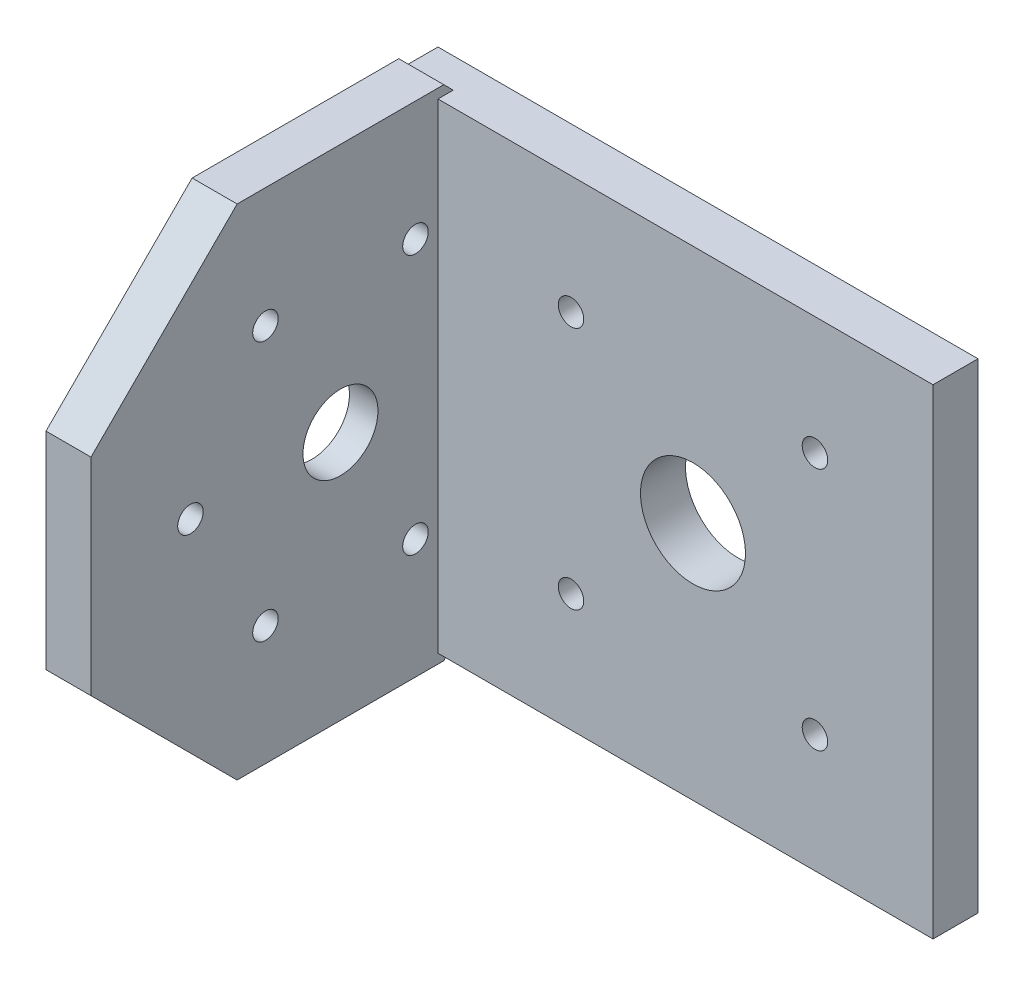
SolidWorks part; units mm, degrees
ref_plane "Front Plane" through (0, 0, 0) normal (0, 0, 1) x (1, 0, 0)
ref_plane "Top Plane" through (0, 0, 0) normal (0, 1, 0) x (1, 0, 0)
ref_plane "Right Plane" through (0, 0, 0) normal (1, 0, 0) x (0, 0, -1)
ref_plane "PL_Roll_Plate_base" through (-40, 0, 0) normal (1, 0, 0) x (0, 0, -1)
sketch "SK_Roll_Plate" plane through (-40, 0, 0) normal (1, 0, 0) x (0, 0, -1)
  line L0 (-13.7766, 33.2597) -> (-33.2597, 13.7766)
  line L1 (-33.2597, 13.7766) -> (-33.2597, -13.7766)
  line L2 (-33.2597, -13.7766) -> (-13.7766, -33.2597)
  line L3 (-13.7766, -33.2597) -> (13.7766, -33.2597)
  line L4 (13.7766, -33.2597) -> (33.2597, -13.7766)
  line L5 (33.2597, -13.7766) -> (33.2597, 13.7766)
  line L6 (33.2597, 13.7766) -> (13.7766, 33.2597)
  line L7 (13.7766, 33.2597) -> (-13.7766, 33.2597)
  circle A0 centre (20, 0) radius 1.7
  circle A1 centre (10, 17.3205) radius 1.7
  circle A2 centre (-10, 17.3205) radius 1.7
  circle A3 centre (-20, 0) radius 1.7
  circle A4 centre (-10, -17.3205) radius 1.7
  circle A5 centre (10, -17.3205) radius 1.7
  circle A6 centre (0, 0) radius 5
  dimension "D17_SK_Roll_Plate" = 3.4
  dimension "D19_SK_Roll_Plate" = 3.4
  dimension "D22_SK_Roll_Plate" = 3.4
  dimension "D25_SK_Roll_Plate" = 3.4
  dimension "D27_SK_Roll_Plate" = 3.4
  dimension "D30_SK_Roll_Plate" = 3.4
  dimension "D33_SK_Roll_Plate" = 10
  dimension "P1" = 13.7766
  dimension "P2" = 33.2597
  dimension "P3" = 33.2597
  dimension "P4" = 13.7766
  dimension "P5" = 33.2597
  dimension "P6" = 13.7766
  dimension "P7" = 13.7766
  dimension "P8" = 33.2597
  dimension "P9" = 13.7766
  dimension "P10" = 33.2597
  dimension "P11" = 33.2597
  dimension "P12" = 13.7766
  dimension "P13" = 33.2597
  dimension "P14" = 13.7766
  dimension "P15" = 13.7766
  dimension "P16" = 33.2597
  dimension "P18" = 20
  dimension "P20" = 10
  dimension "P21" = 17.3205
  dimension "P23" = 10
  dimension "P24" = 17.3205
  dimension "P26" = 20
  dimension "P28" = 10
  dimension "P29" = 17.3205
  dimension "P31" = 10
  dimension "P32" = 17.3205
extrude "Roll_Plate" add sketch "SK_Roll_Plate" along normal blind 6
ref_plane "PL_Yaw_Plate_base" through (0, 0, -19) normal (0, 0, 1) x (1, 0, 0)
sketch "SK_Yaw_Plate" plane through (0, 0, -19) normal (0, 0, 1) x (1, 0, 0)
  line L0 (-40, -32) -> (32, -32)
  line L1 (32, -32) -> (32, 32)
  line L2 (32, 32) -> (-40, 32)
  line L3 (-40, 32) -> (-40, -32)
  circle A0 centre (16.2635, 16.2635) radius 1.7
  circle A1 centre (-16.2635, 16.2635) radius 1.7
  circle A2 centre (-16.2635, -16.2635) radius 1.7
  circle A3 centre (16.2635, -16.2635) radius 1.7
  circle A4 centre (0, 0) radius 7
  dimension "D9_SK_Yaw_Plate" = 3.4
  dimension "D12_SK_Yaw_Plate" = 3.4
  dimension "D15_SK_Yaw_Plate" = 3.4
  dimension "D18_SK_Yaw_Plate" = 3.4
  dimension "D21_SK_Yaw_Plate" = 14
  dimension "P1" = 40
  dimension "P2" = 32
  dimension "P3" = 32
  dimension "P4" = 32
  dimension "P5" = 32
  dimension "P6" = 32
  dimension "P7" = 40
  dimension "P8" = 32
  dimension "P10" = 16.2635
  dimension "P11" = 16.2635
  dimension "P13" = 16.2635
  dimension "P14" = 16.2635
  dimension "P16" = 16.2635
  dimension "P17" = 16.2635
  dimension "P19" = 16.2635
  dimension "P20" = 16.2635
extrude "Yaw_Plate" add sketch "SK_Yaw_Plate" along normal blind 6
ref_plane "PL_Roll_Pilot_Recess_base" through (-40, 0, 0) normal (1, 0, 0) x (0, 0, -1)
sketch "SK_Roll_Pilot_Recess" plane through (-40, 0, 0) normal (1, 0, 0) x (0, 0, -1)
  circle A0 centre (0, 0) radius 15.15
  dimension "D1_SK_Roll_Pilot_Recess" = 30.3
extrude "Roll_Pilot_Recess" cut sketch "SK_Roll_Pilot_Recess" along normal blind 2.2
equation "\"Roll_face_x\" = -40"
equation "\"Yaw_rear_z\" = -19"
